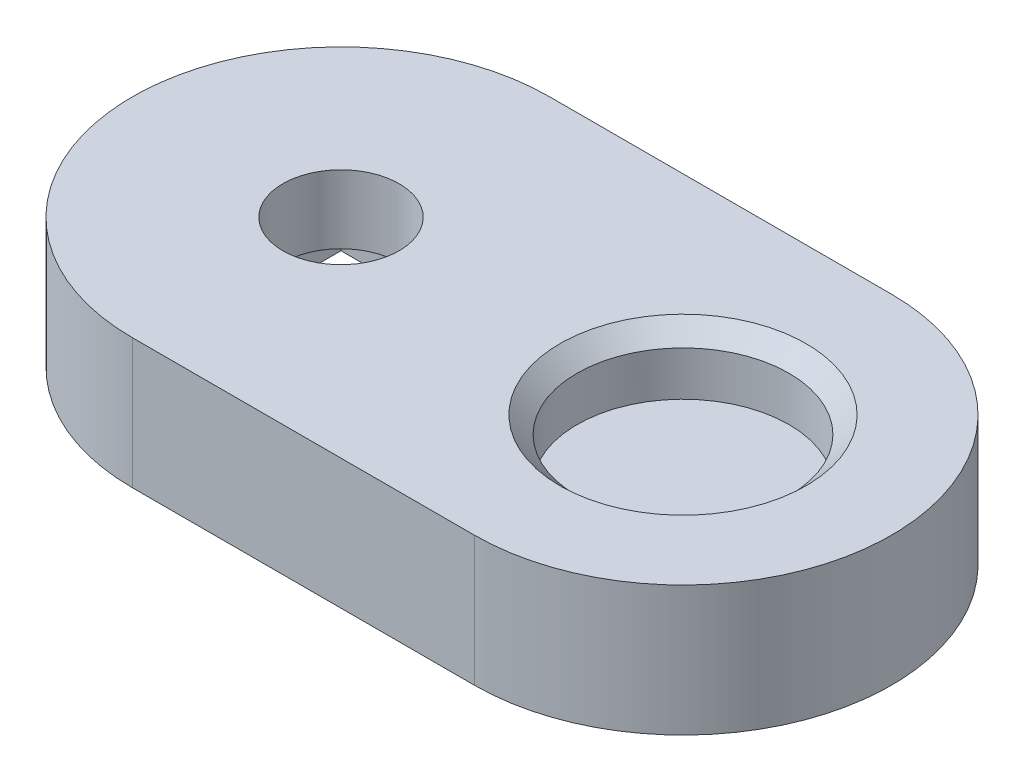
SolidWorks part; units mm, degrees
ref_plane "Front Plane" through (0, 0, 0) normal (0, 0, 1) x (1, 0, 0)
ref_plane "Top Plane" through (0, 0, 0) normal (0, 1, 0) x (1, 0, 0)
ref_plane "Right Plane" through (0, 0, 0) normal (1, 0, 0) x (0, 0, -1)
sketch "Sketch1" plane through (0, 0, 0) normal (0, 1, 0) x (1, 0, 0)
  line L0 (-5, 0) -> (5, 0) construction
  line L1 (-5, 6.1) -> (5, 6.1)
  line L2 (-5, -6.1) -> (5, -6.1)
  line L4 (-7.95, -2.95) -> (-2.05, -2.95)
  line L5 (-7.95, -2.95) -> (-7.95, 2.95)
  line L6 (-7.95, 2.95) -> (-2.05, 2.95)
  line L7 (-2.05, -2.95) -> (-2.05, 2.95)
  line L8 (-7.95, -2.95) -> (-2.05, 2.95) construction
  line L9 (-7.95, 2.95) -> (-2.05, -2.95) construction
  arc A0 (-5, 6.1) -> (-5, -6.1) centre (-5, 0) ccw
  arc A1 (5, -6.1) -> (5, 6.1) centre (5, 0) ccw
  circle A2 centre (5, 0) radius 3.1
  point P2 (0, 0)
  point P10 (-5, 0)
  dimension "D1" = 6.2
  dimension "D2" = 5.9
  dimension "D3" = 3
  dimension "D4" = 10
extrude "Boss-Extrude1" add sketch "Sketch1" along normal blind 3.8
sketch "Sketch2" plane through (0, 3.8, 0) normal (0, 1, 0) x (1, 0, 0)
  line L0 (-2.05, 2.95) -> (-7.95, 2.95) construction
  line L1 (-7.95, 2.95) -> (-2.05, 2.95)
  line L2 (-7.95, 2.95) -> (-7.95, -2.95)
  line L3 (-7.95, -2.95) -> (-2.05, -2.95)
  line L4 (-2.05, 2.95) -> (-2.05, -2.95)
  line L5 (-7.95, 2.95) -> (-2.05, -2.95) construction
  line L6 (-7.95, -2.95) -> (-2.05, 2.95) construction
  line L7 (-7.95, 2.95) -> (-7.95, -2.95) construction
  line L8 (-2.05, -2.95) -> (-2.05, 2.95) construction
  line L9 (-7.95, -2.95) -> (-2.05, -2.95) construction
  circle A0 centre (-5, 0) radius 1.7
  point P0 (-5, 0)
  dimension "D1" = 3.4
extrude "Boss-Extrude2" add sketch "Sketch2" against normal offset from surface (2 mm away) 1.8 up to face at (5, 0, 3.1)
sketch "Sketch3" plane through (0, 0, 0) normal (0, -1, 0) x (1, 0, 0)
  circle A0 centre (5, 0) radius 3.1
  circle A2 centre (5, 0) radius 3.1 construction
extrude "Boss-Extrude3" add sketch "Sketch3" against normal offset from surface (2 mm away) 1.8 up to face at (0, 3.8, 0)
chamfer "Chamfer1" distance 0.5 angle 45 1 edges at (5, 3.8, 3.1)
equation "\"magnet_d\"= 6.2"
equation "\"magnet_t\"= 1.8"
equation "\"M3_nut_s\"= 5.9"
equation "\"M3_nut_m\"= 1.8"
equation "\"M3_d\"= 3.4"
equation "\"t\"= 3"
equation "\"D1@Sketch1\"=\"magnet_d\""
equation "\"D2@Sketch1\"=\"M3_nut_s\""
equation "\"D3@Sketch1\"=\"t\""
equation "\"D1@Boss-Extrude1\"=\"magnet_t\" + 2/3 * \"t\""
equation "\"D1@Boss-Extrude2\"=\"M3_nut_m\""
equation "\"D1@Boss-Extrude3\"=\"magnet_t\""
equation "\"D1@Sketch2\"=\"M3_d\""
